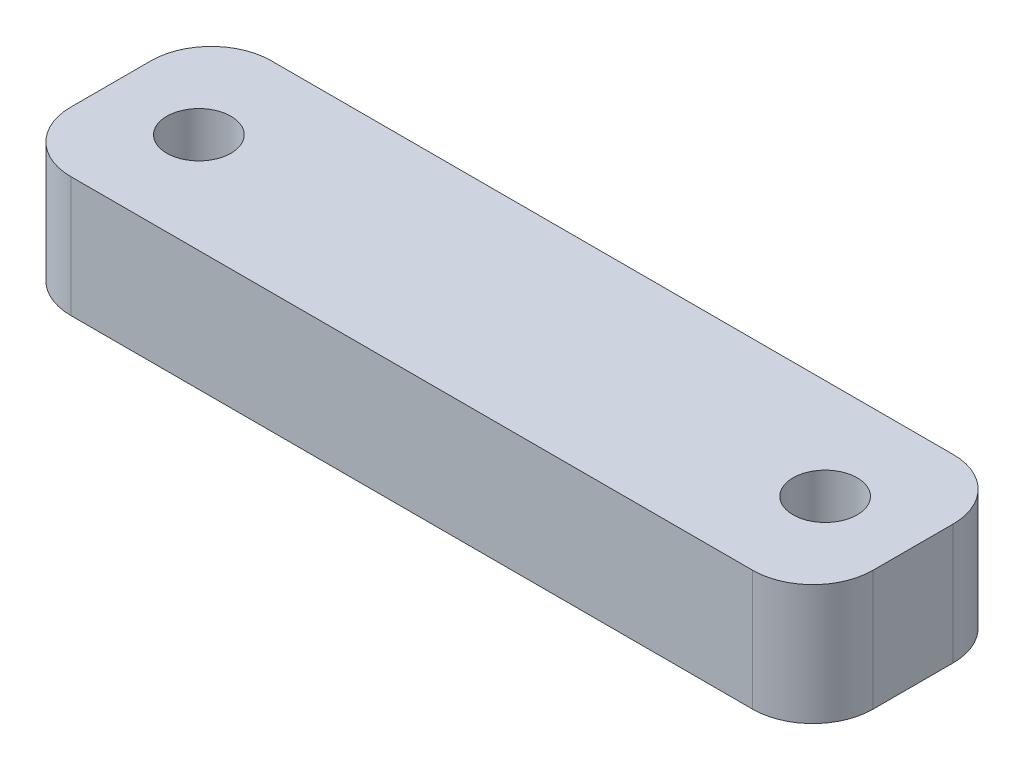
SolidWorks part; units mm, degrees
ref_plane "前视基准面" through (0, 0, 0) normal (0, 0, 1) x (1, 0, 0)
ref_plane "上视基准面" through (0, 0, 0) normal (0, 1, 0) x (1, 0, 0)
ref_plane "右视基准面" through (0, 0, 0) normal (1, 0, 0) x (0, 0, -1)
sketch "草图1" plane through (0, 0, 0) normal (0, 1, 0) x (1, 0, 0)
  line L1 (-20, -5) -> (20, -5)
  line L2 (-20, -5) -> (-20, 5)
  line L3 (-20, 5) -> (20, 5)
  line L4 (20, -5) -> (20, 5)
  line L5 (-20, -5) -> (20, 5) construction
  line L6 (-20, 5) -> (20, -5) construction
  point P0 (0, 0)
  dimension "D1" = 10
  dimension "D2" = 40
extrude "凸台-拉伸1" add sketch "草图1" along normal blind 6
sketch "草图2" plane through (0, 6, 0) normal (0, 1, 0) x (1, 0, 0)
  line L0 (-21.5324, 0) -> (23.1173, 0) construction
  line L1 (0, 10.7662) -> (0, -11.5313) construction
  circle A0 centre (-15.6125, 0) radius 1.6
  circle A1 centre (15.6125, 0) radius 1.6
  dimension "D1" = 3.2
  dimension "D2" = 31.225
extrude "切除-拉伸1" cut sketch "草图2" against normal up to next
sketch "草图3" plane through (0, 0, 0) normal (0, -1, 0) x (1, 0, 0)
  point P0 (15.6125, 0)
fillet "圆角1" radius 3 4 edges at (20, 3, 5) (-20, 3, 5) (-20, 3, -5) (20, 3, -5)
